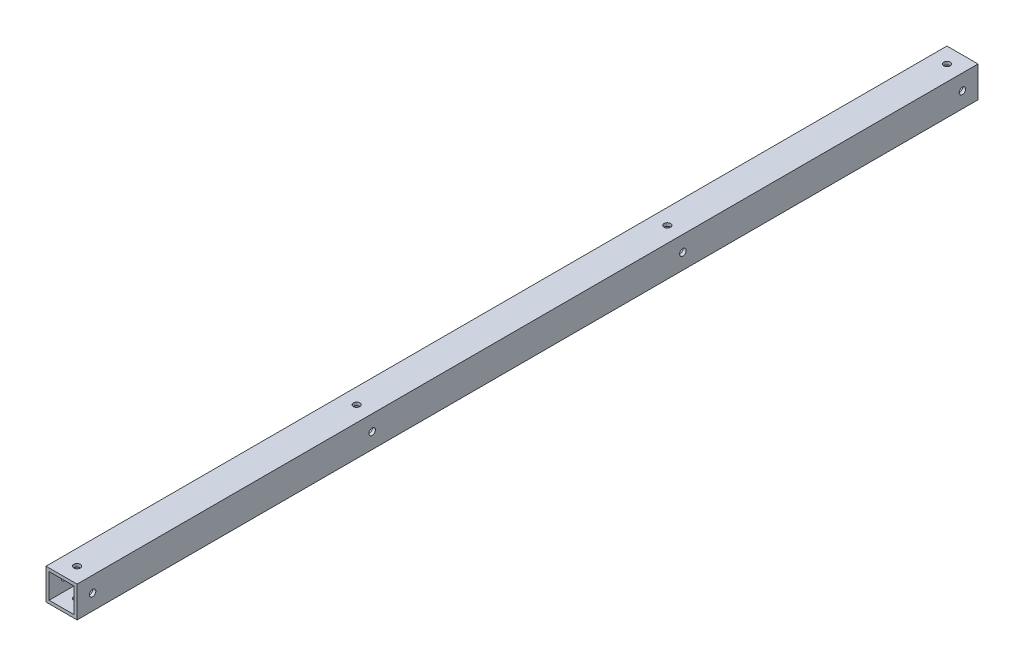
SolidWorks part; units mm, degrees
ref_plane "前视基准面" through (0, 0, 0) normal (0, 0, 1) x (1, 0, 0)
ref_plane "上视基准面" through (0, 0, 0) normal (0, 1, 0) x (1, 0, 0)
ref_plane "右视基准面" through (0, 0, 0) normal (1, 0, 0) x (0, 0, -1)
other "Configuration Table"
sketch "草图1" plane through (0, 0, 0) normal (0, 0, 1) x (1, 0, 0)
  line L1 (-10, -10) -> (10, -10)
  line L2 (-10, -10) -> (-10, 10)
  line L3 (-10, 10) -> (10, 10)
  line L4 (10, -10) -> (10, 10)
  line L5 (-10, -10) -> (10, 10) construction
  line L6 (-10, 10) -> (10, -10) construction
  line L7 (-8, -8) -> (8, -8)
  line L8 (-8, -8) -> (-8, 8)
  line L9 (-8, 8) -> (8, 8)
  line L10 (8, -8) -> (8, 8)
  line L11 (-8, -8) -> (8, 8) construction
  line L12 (-8, 8) -> (8, -8) construction
  point P0 (0, 0)
  point P6 (0, 0)
  dimension "D1" = 20
  dimension "D2" = 2
extrude "凸台-拉伸1" add sketch "草图1" along normal blind 580 contours L1 L4 L3 L2 L10 L7 L8 L9
sketch "草图2" plane through (0, 10, 0) normal (0, 1, 0) x (1, 0, 0)
  line L0 (0, 0) -> (0, -119.3181) construction
  line L1 (-10, 0) -> (10, 0) construction
  circle A0 centre (0, -10) radius 2.1
  circle A1 centre (0, -190) radius 2.1
  dimension "D1" = 4.2
  dimension "D3" = 4.2
  dimension "D2" = 10
  dimension "D4" = 190
ref_plane "基准面1" through (0, 0, 290) normal (0, 0, 1) x (1, 0, 0)
extrude "切除-拉伸1" cut sketch "草图2" against normal blind 20 contours A0 | A1
mirror "镜向1" about plane through (0, 0, 290) normal (0, 0, 1) of "切除-拉伸1"
ref_plane "基准面2" through (10, 10, 580) normal (1, 0, 0) x (0, 0, -1)
sketch "草图3" plane through (10, 10, 580) normal (1, 0, 0) x (0, 0, -1)
  line L0 (0, -20) -> (0, 0) construction
  line L1 (0, -20) -> (580, -20) construction
  line L2 (0, 0) -> (580, 0) construction
  line L3 (580, -20) -> (580, 0) construction
  line L4 (0, -10) -> (580, -10) construction
  line L5 (290, 1) -> (290, -21) construction
  circle A0 centre (10, -10) radius 2.1
  circle A1 centre (570, -10) radius 2.1
  circle A2 centre (190, -10) radius 2.1
  circle A3 centre (390, -10) radius 2.1
  dimension "D1" = 4.2
  dimension "D4" = 4.2
  dimension "D8" = 4.2
  dimension "D2" = 10
  dimension "D3" = 10
  dimension "D5" = 10
  dimension "D6" = 10
  dimension "D7" = 190
extrude "切除-拉伸2" cut sketch "草图3" against normal through all
